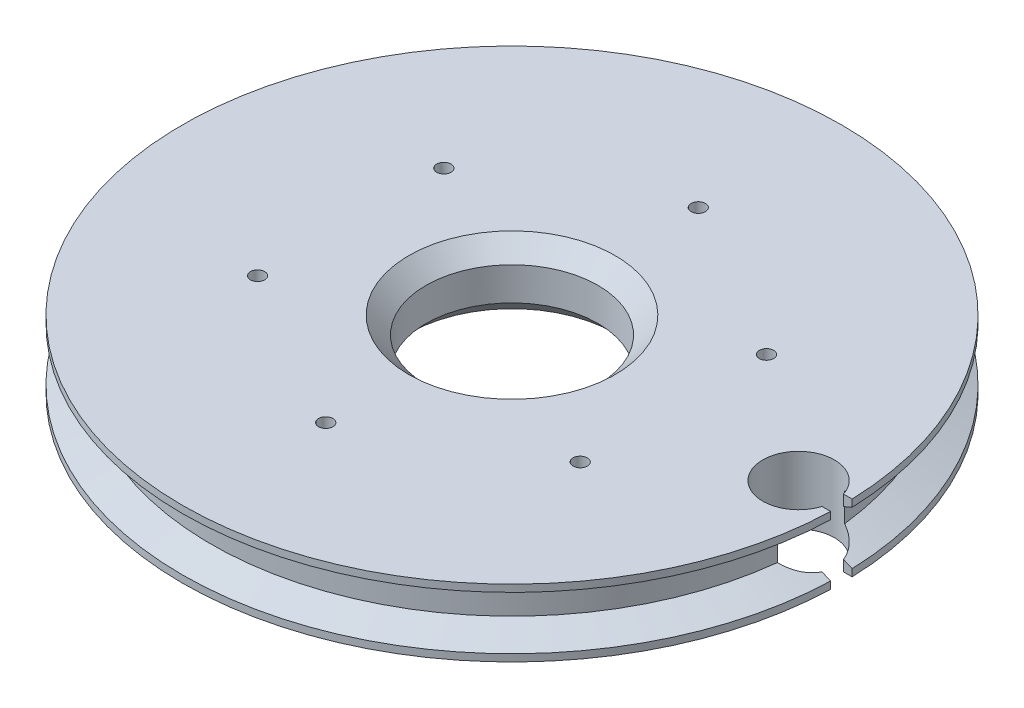
SolidWorks part; units mm, degrees
ref_plane "Plano frontal" through (0, 0, 0) normal (0, 0, 1) x (1, 0, 0)
ref_plane "Plano superior" through (0, 0, 0) normal (0, 1, 0) x (1, 0, 0)
ref_plane "Plano direito" through (0, 0, 0) normal (1, 0, 0) x (0, 0, -1)
sketch "Esboço2" plane through (0, 0, 0) normal (0, 0, 1) x (1, 0, 0)
  line L0 (6, 0) -> (23, 0)
  line L1 (23, 0) -> (23, 0.5)
  line L2 (23, 0.5) -> (21, 1.3527)
  line L3 (21, 1.3527) -> (21, 3.3527)
  line L4 (21, 3.3527) -> (23, 4.2053)
  line L5 (23, 4.2053) -> (23, 4.7053)
  line L8 (23, 4.7053) -> (6, 4.7053)
  line L11 (6, 4.7053) -> (6, 0)
  line L12 (0, 0) -> (0, 4.7053) construction
  dimension "D1" = 23
  dimension "D2" = 2
  dimension "D3" = 0.5
  dimension "D4" = 0.5
  dimension "D5" = 2
  dimension "D6" = 2
  dimension "D7" = 6
  dimension "D8" = 17
  dimension "D9" = 4.7053
  dimension "D10" = 113.09
  dimension "D11" = 113.09
revolve "Revolução1" add sketch "Esboço2" angle 360 about L12
sketch "Esboço3" plane through (0, 0, 0) normal (0, -1, 0) x (1, 0, 0)
  line L0 (20, 0) -> (25.9427, 0) construction
  line L1 (23.115, 0.75) -> (23.115, -0.75)
  line L2 (23.115, 0.75) -> (22.3848, 0.75)
  line L3 (23.115, -0.75) -> (22.3848, -0.75)
  arc A1 (22.3848, 0.75) -> (22.3848, -0.75) centre (20, 0) ccw
  point P8 (23.115, 0)
  dimension "D1" = 5
  dimension "D2" = 20
  dimension "D3" = 1.5
  dimension "D4" = 3.115
extrude "Corte-extrusão1" cut sketch "Esboço3" against normal blind 10
chamfer "Chanfro3" distance 1.2 angle 45 2 edges at (0, 0, -6) (0, 4.7053, -6)
sketch "Esboço5" plane through (0, 4.7053, 0) normal (0, 1, 0) x (1, 0, 0)
  circle A0 centre (0, 13) radius 0.5
  circle A1 centre (0, -13) radius 0.5
  circle A2 centre (0, 0) radius 13
  circle A4 centre (11.2583, 6.5) radius 0.5
  circle A5 centre (-11.2583, -6.5) radius 0.5
  circle A6 centre (11.2583, -6.5) radius 0.5
  circle A7 centre (-11.2583, 6.5) radius 0.5
  circle A8 centre (0, -13) radius 0.5
  circle A9 centre (0, 13) radius 0.5
  circle A10 centre (-11.2583, -6.5) radius 0.5
  circle A11 centre (11.2583, 6.5) radius 0.5
  circle A12 centre (-11.2583, 6.5) radius 0.5
  circle A13 centre (11.2583, -6.5) radius 0.5
  point P29 (0, 0)
  dimension "D1" = 1
  dimension "D3" = 1
  dimension "D5" = 26
  dimension "D2" = 6
extrude "Corte-extrusão2" cut sketch "Esboço5" against normal through all both and the other way through all contours A0 | A7 | A5 | A4 | A6 | A1
